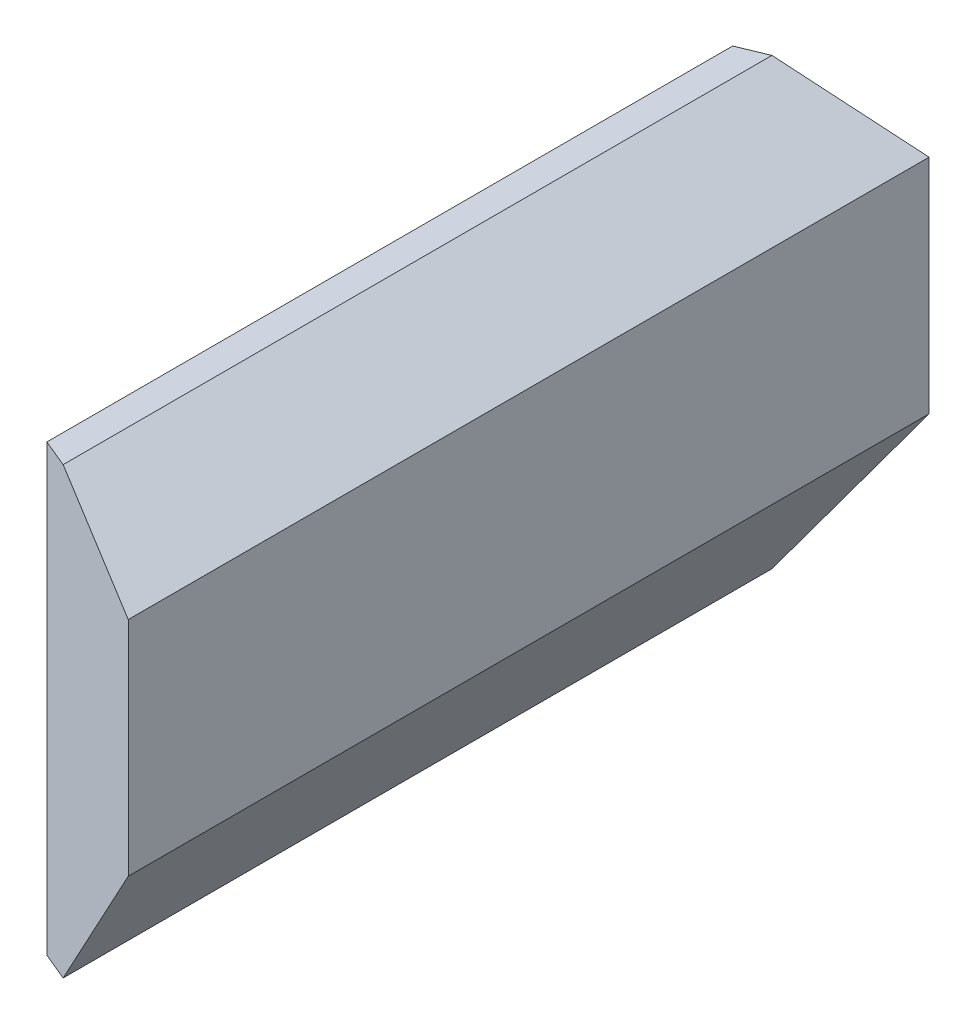
SolidWorks part; units mm, degrees
material "橡胶"
ref_plane "前视基准面" through (0, 0, 0) normal (0, 0, 1) x (1, 0, 0)
ref_plane "上视基准面" through (0, 0, 0) normal (0, 1, 0) x (1, 0, 0)
ref_plane "右视基准面" through (0, 0, 0) normal (1, 0, 0) x (0, 0, -1)
sketch "草图1" plane through (0, 0, 0) normal (0, 0, 1) x (1, 0, 0)
  line L0 (0, 40) -> (0, 50)
  line L1 (0, 40) -> (25, 40) construction
  line L2 (0, 0) -> (0, 40)
  line L3 (0, 0) -> (25, 0) construction
  line L4 (25, 0) -> (25, 40)
  line L5 (0, 50) -> (25, 40) construction
  line L6 (0, 0) -> (0, -30)
  line L7 (0, -30) -> (25, 0) construction
  line L8 (0, 50) -> (5, 50)
  line L9 (5, 50) -> (25, 40)
  line L10 (25, 0) -> (5, -30)
  line L11 (5, -30) -> (0, -30)
  dimension "D1" = 25
  dimension "D2" = 40
  dimension "D4" = 10
  dimension "D5" = 5
  dimension "D6" = 5
  dimension "D7" = 80
extrude "拉伸1" add sketch "草图1" along normal blind 150
sketch "草图2" plane through (0, 50, 0) normal (0, 1, 0) x (-1, 0, 0)
  line L0 (0, 75) -> (-51.0039, 75) construction
  line L1 (0, 150) -> (0, 0) construction
  line L2 (0, 13.3) -> (-66.2619, -14.1466)
  line L3 (-66.2619, -14.1466) -> (0, -14.1466)
  line L4 (0, -14.1466) -> (0, 13.3)
  line L5 (0, 136.7) -> (-66.2619, 164.1466)
  line L6 (-66.2619, 164.1466) -> (0, 164.1466)
  line L7 (0, 164.1466) -> (0, 136.7)
  dimension "D1" = 123.4
  dimension "D2" = 67.5
extrude "切除-拉伸1" cut sketch "草图2" against normal up to next
sketch "草图3" plane through (0, 0, 0) normal (-1, 0, 0) x (0, 0, 1)
  line L0 (75, 50) -> (75, -39.2067) construction
  line L1 (136.7, 50) -> (13.3, 50) construction
  line L2 (13.3, -30) -> (13.3, 50) construction
  line L3 (71.3, 45) -> (18.3, 45)
  line L4 (71.3, 45) -> (71.3, -25)
  line L5 (71.3, -25) -> (18.3, -25)
  line L6 (18.3, 45) -> (18.3, -25)
  line L7 (78.7, 45) -> (131.7, 45)
  line L8 (78.7, 45) -> (78.7, -25)
  line L9 (78.7, -25) -> (131.7, -25)
  line L10 (131.7, 45) -> (131.7, -25)
  line L11 (13.3, 10) -> (158.6129, 10) construction
  dimension "D1" = 5
  dimension "D2" = 53
  dimension "D3" = 70
ref_plane "基准面1" through (0, 0, 18.3) normal (0, 0, -1) x (-1, 0, 0)
ref_plane "基准面2" through (0, 0, 131.7) normal (0, 0, -1) x (-1, 0, 0)
sketch "草图4" plane through (0, 0, 18.3) normal (0, 0, -1) x (-1, 0, 0)
  line L0 (0, 45) -> (-6.0557, 45)
  line L1 (0, 45) -> (0, -25) construction
  line L2 (-6.0557, 45) -> (-21, 37.5279)
  line L3 (-21, 37.5279) -> (-21, 1.2111)
  line L4 (-21, 1.2111) -> (-3.5259, -25)
  line L5 (-3.5259, -25) -> (0, -25)
  line L6 (0, -25) -> (0, 45)
  line L7 (-5, 50) -> (-25, 40) construction
  line L8 (-25, 0) -> (-5, -30) construction
  line L9 (0, 50) -> (-5, 50) construction
  line L10 (-25, 40) -> (-25, 0) construction
  line L11 (-5, -30) -> (0, -30) construction
  dimension "D1" = 5
  dimension "D2" = 4
  dimension "D3" = 4
  dimension "D4" = 4
  dimension "D5" = 5
extrude "切除-拉伸2" cut sketch "草图4" against normal blind 53
sketch "草图5" plane through (0, 0, 131.7) normal (0, 0, -1) x (-1, 0, 0)
  line L0 (0, 45) -> (-6.0557, 45)
  line L1 (-6.0557, 45) -> (-21, 37.5279)
  line L2 (-21, 37.5279) -> (-21, 1.2111)
  line L3 (-21, 1.2111) -> (-3.5259, -25)
  line L4 (-3.5259, -25) -> (0, -25)
  line L5 (0, -25) -> (0, 45)
extrude "切除-拉伸3" cut sketch "草图5" along normal blind 53
